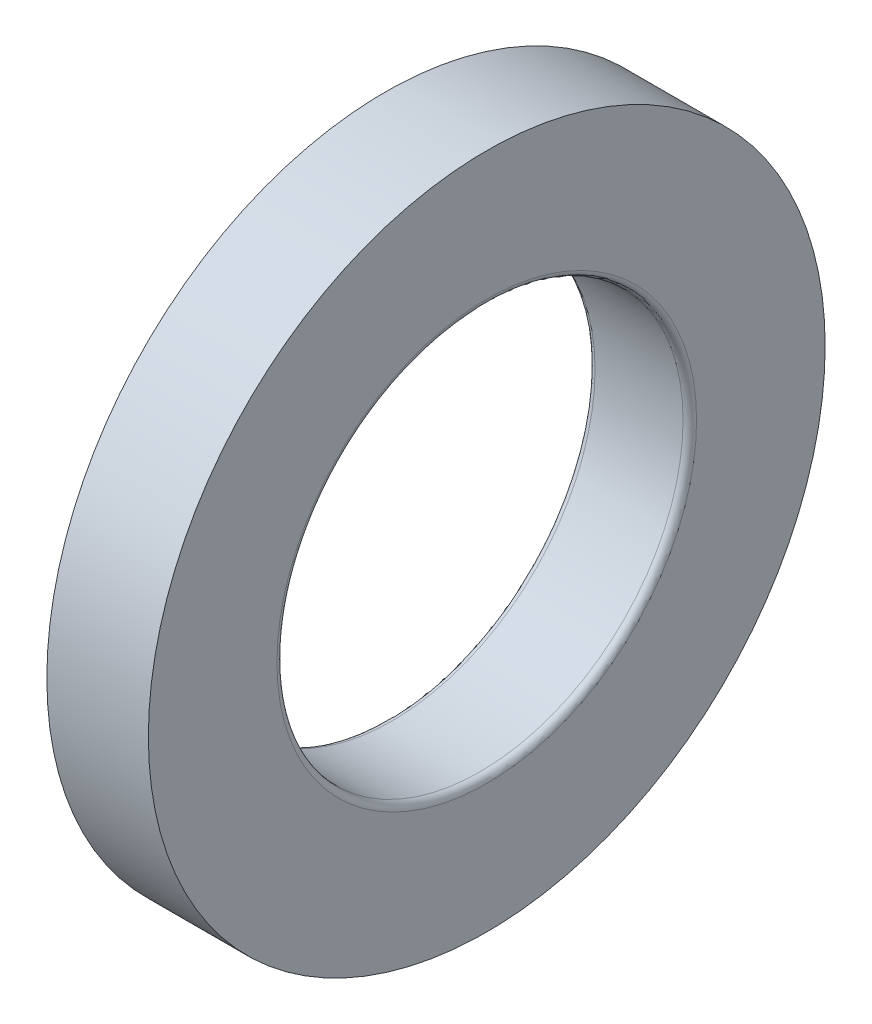
SolidWorks part; units mm, degrees
material "POLIURETANO (11671)"
ref_plane "Plano frontal" through (0, 0, 0) normal (0, 0, 1) x (1, 0, 0)
ref_plane "Plano superior" through (0, 0, 0) normal (0, 1, 0) x (1, 0, 0)
ref_plane "Plano direito" through (0, 0, 0) normal (1, 0, 0) x (0, 0, -1)
sketch "Esboço2" plane through (0, 0, 0) normal (1, 0, 0) x (0, 0, -1)
  circle A0 centre (0, 0) radius 50
  dimension "D1" = 100
extrude "Ressalto-extrusão1" add sketch "Esboço2" along normal blind 15
sketch "Esboço3" plane through (15, 0, 0) normal (1, 0, 0) x (0, 0, -1)
  circle A0 centre (0, 0) radius 30
  dimension "D1" = 60
extrude "Corte-extrusão1" cut sketch "Esboço3" against normal through all
fillet "Filete1" radius 1 2 edges at (15, 0, -30) (0, 0, -30)
